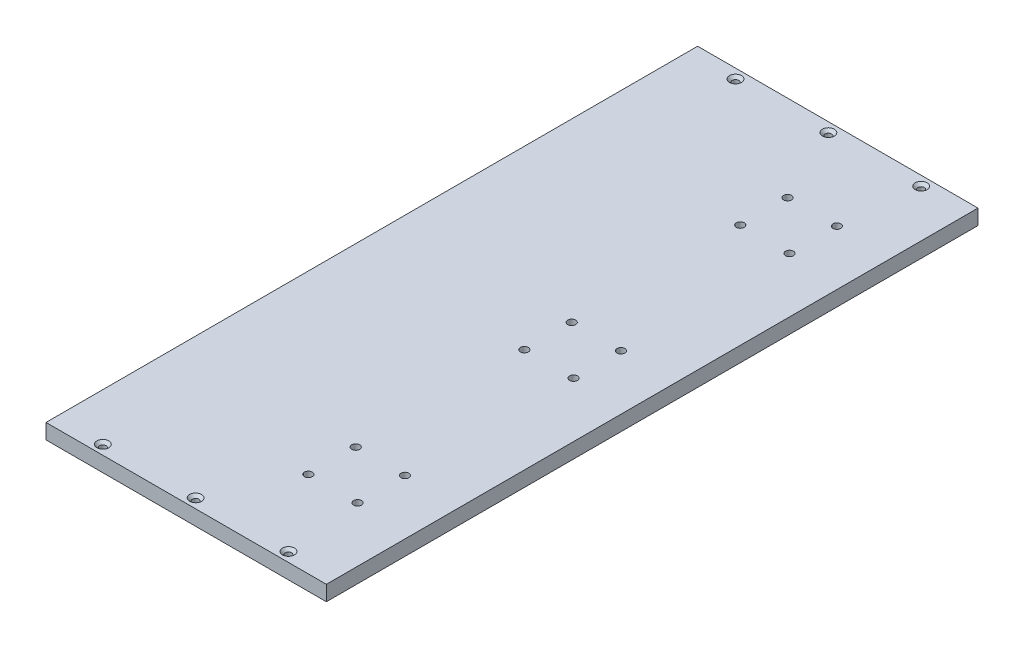
SolidWorks part; units mm, degrees
ref_plane "Front Plane" through (0, 0, 0) normal (0, 0, 1) x (1, 0, 0)
ref_plane "Top Plane" through (0, 0, 0) normal (0, 1, 0) x (1, 0, 0)
ref_plane "Right Plane" through (0, 0, 0) normal (1, 0, 0) x (0, 0, -1)
sketch "Sketch1" plane through (0, 0, 0) normal (0, 1, 0) x (1, 0, 0)
  line L1 (-74, -172) -> (74, -172)
  line L2 (-74, -172) -> (-74, 172)
  line L3 (-74, 172) -> (74, 172)
  line L4 (74, -172) -> (74, 172)
  line L5 (-74, -172) -> (74, 172) construction
  line L6 (-74, 172) -> (74, -172) construction
  point P0 (0, 0)
  dimension "D1" = 344
  dimension "D2" = 148
extrude "Boss-Extrude1" add sketch "Sketch1" along normal blind 8
sketch "Sketch2" plane through (0, 8, 0) normal (0, 1, 0) x (1, 0, 0)
  line L0 (74, -167) -> (-74, -167) construction
  line L1 (74, -172) -> (74, 172) construction
  line L2 (-74, 172) -> (-74, -172) construction
  line L3 (-74, -172) -> (74, -172) construction
  point P8 (0, -167)
  point P9 (-49, -167)
  point P10 (49, -167)
  dimension "D1" = 5
  dimension "D2" = 49
  dimension "D3" = 49
hole_wizard "CSK for M3 Countersunk Flat Head1" positions "3DSketch1" profile "Sketch3" countersink size "M3" standard "BSI"
sketch3d "3DSketch1"
  point P0 (-49, 8, 167)
  point P3 (0, 8, 167)
  point P6 (49, 8, 167)
sketch "Sketch3" plane through (-49, 8, 167) normal (1, 0, 0) x (0, 0, 1)
  line L0 (0, 0) -> (0, 16.0215)
  line L1 (0, 16.0215) -> (1.7, 15)
  line L2 (1.7, 15) -> (1.7, 1.45)
  line L3 (1.7, 1.45) -> (3.15, 0)
  line L5 (3.15, 0) -> (0, 0)
  line L6 (-1.7, 1.45) -> (-3.15, 0) construction
  line L10 (0, 16.0215) -> (-1.7, 15) construction
  line L11 (0, -6.35) -> (0, 107.95) construction
  dimension "Hole Dia." = 3.4
  dimension "Hole Depth" = 15
  dimension "Near C'Sink Dia." = 6.3
  dimension "Near C'Sink Angle" = 90
  dimension "Drill Angle" = 118
mirror "Mirror1" about plane through (0, 0, 0) normal (0, 0, 1) of "CSK for M3 Countersunk Flat Head1"
sketch "Sketch4" plane through (0, 8, 0) normal (0, 1, 0) x (1, 0, 0)
  line L0 (88, 0) -> (45, 0) construction
  line L1 (74, -172) -> (74, 172) construction
  line L2 (81, 172) -> (81, -172) construction
  line L3 (74, 172) -> (-74, 172) construction
  line L4 (-74, -172) -> (74, -172) construction
  line L5 (88, 172) -> (88, -172) construction
  line L6 (45, 12.5) -> (45, -12.5) construction
  line L7 (0, 0) -> (45, 0) construction
  line L8 (45, -12.5) -> (19, -12.5) construction
  line L9 (45, 12.5) -> (19, 12.5) construction
  dimension "D1" = 7
  dimension "D2" = 7
  dimension "D3" = 36
  dimension "D4" = 26
  dimension "D5" = 26
  dimension "D6" = 25
hole_wizard "M5x0.8 Tapped Hole1" positions "3DSketch2" profile "Sketch5" tap size "M5x0.8" standard "BSI" end condition through all
sketch3d "3DSketch2"
  point P0 (45, 8, -12.5)
  point P3 (19, 8, -12.5)
  point P6 (19, 8, 12.5)
  point P9 (45, 8, 12.5)
sketch "Sketch5" plane through (45, 8, -12.5) normal (1, 0, 0) x (0, 0, 1)
  line L0 (0, 0) -> (0, 8)
  line L1 (0, 8) -> (2.1, 8)
  line L2 (2.1, 8) -> (2.1, 0)
  line L5 (2.1, 0) -> (0, 0)
  line L11 (0, -6.35) -> (0, 107.95) construction
  dimension "Thru Tap Drill Dia." = 4.2
  dimension "Thru Tap Drill Depth" = 8
cosmetic thread "Hole Thread1" parameters "D2"=5
cosmetic thread "Hole Thread2" parameters "D2"=5
cosmetic thread "Hole Thread3" parameters "D2"=5
cosmetic thread "Hole Thread4" parameters "D2"=5
pattern_linear "LPattern1" count 2 spacing 114 along (0, 0, 1) count 2 spacing 114 along (0, 0, -1) of "M5x0.8 Tapped Hole1"
